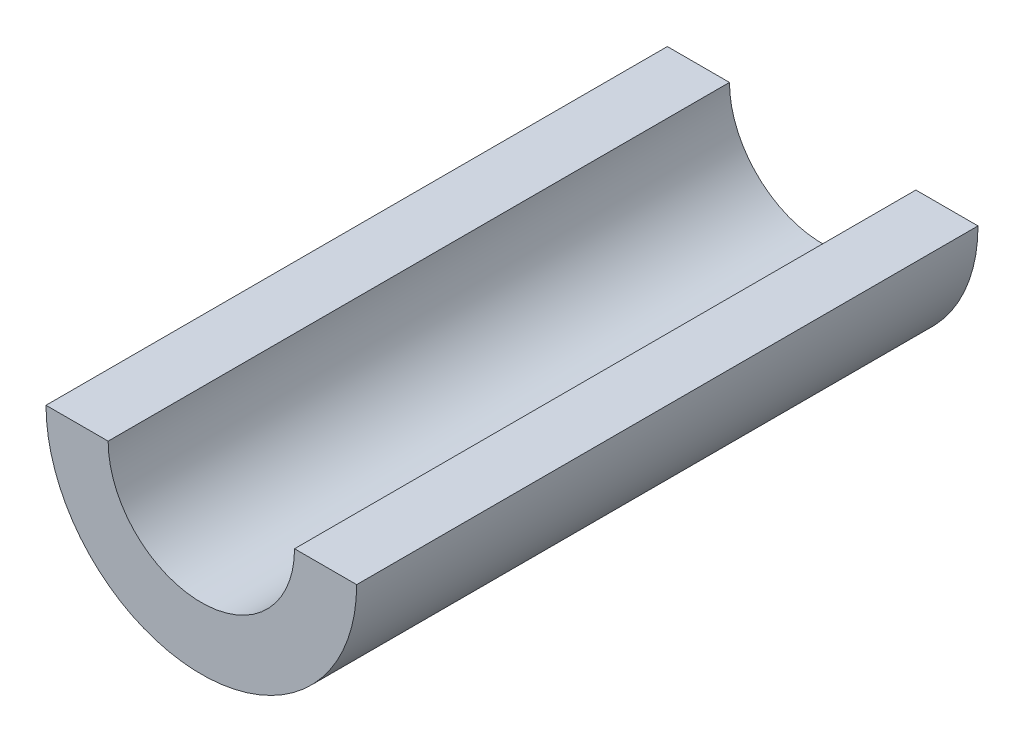
SolidWorks part; units mm, degrees
ref_plane "Alzado" through (0, 0, 0) normal (0, 0, 1) x (1, 0, 0)
ref_plane "Planta" through (0, 0, 0) normal (0, 1, 0) x (1, 0, 0)
ref_plane "Vista lateral" through (0, 0, 0) normal (1, 0, 0) x (0, 0, -1)
sketch "Croquis1" plane through (0, 0, 0) normal (0, 0, 1) x (1, 0, 0)
  line L0 (-10, 0) -> (-6, 0)
  line L1 (6, 0) -> (10, 0)
  arc A0 (6, 0) -> (-6, 0) centre (0, 0) cw
  arc A1 (10, 0) -> (-10, 0) centre (0, 0) cw
extrude "Saliente-Extruir1" add sketch "Croquis1" along normal blind 40
